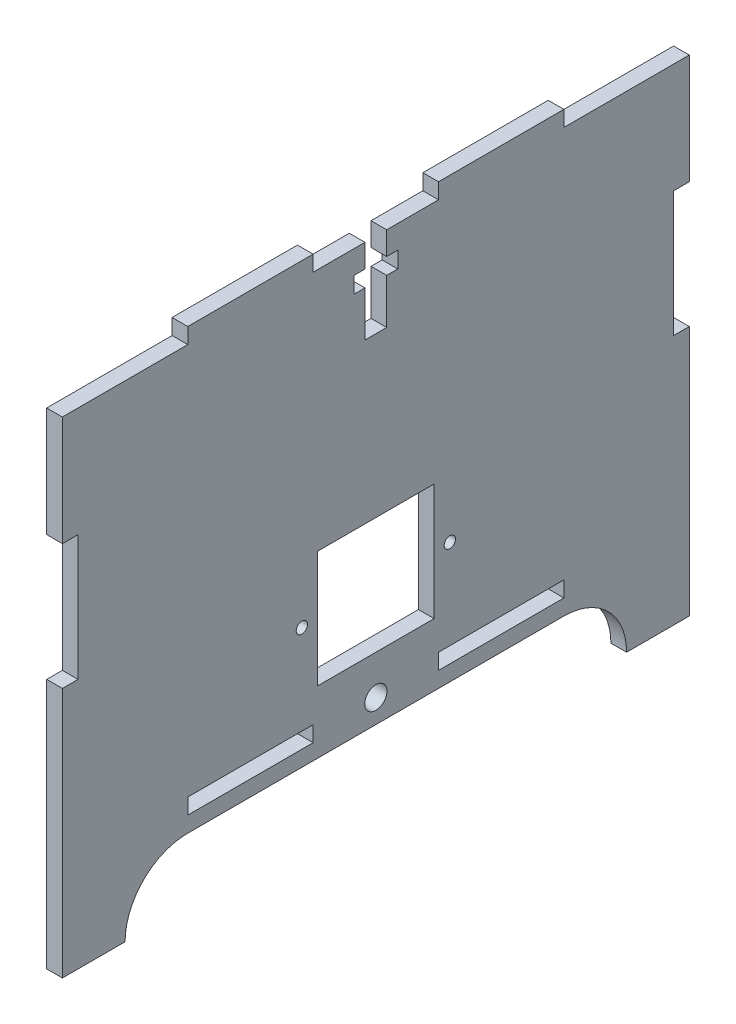
SolidWorks part; units mm, degrees
ref_plane "Front Plane" through (0, 0, 0) normal (0, 0, 1) x (1, 0, 0)
ref_plane "Top Plane" through (0, 0, 0) normal (0, 1, 0) x (1, 0, 0)
ref_plane "Right Plane" through (0, 0, 0) normal (1, 0, 0) x (0, 0, -1)
sketch "Sketch1" plane through (0, 0, 0) normal (1, 0, 0) x (0, 0, -1)
  line L1 (-63.5, 50.8) -> (63.5, 50.8)
  line L2 (-63.5, 50.8) -> (-63.5, -50.8)
  line L3 (-63.5, -50.8) -> (63.5, -50.8)
  line L4 (63.5, 50.8) -> (63.5, -50.8)
  line L5 (-63.5, 50.8) -> (63.5, -50.8) construction
  line L6 (-63.5, -50.8) -> (63.5, 50.8) construction
  point P0 (0, 0)
  dimension "D1" = 127
  dimension "D2" = 101.6
extrude "Boss-Extrude1" add sketch "Sketch1" along normal blind 3.175
sketch "Sketch2" plane through (3.175, 0, 0) normal (1, 0, 0) x (0, 0, -1)
  line L1 (-63.5, 50.8) -> (-38.1, 50.8)
  line L2 (-63.5, 50.8) -> (-63.5, 47.625)
  line L3 (-63.5, 47.625) -> (-38.1, 47.625)
  line L4 (-38.1, 50.8) -> (-38.1, 47.625)
  dimension "D1" = 25.4
  dimension "D2" = 3.175
extrude "Cut-Extrude1" cut sketch "Sketch2" against normal blind 6.35
pattern_linear "LPattern1" count 3 spacing 50.8 along (0, 0, -1) of "Cut-Extrude1"
sketch "Sketch5" plane through (3.175, 0, 0) normal (1, 0, 0) x (0, 0, -1)
  line L0 (-38.1, -50.8) -> (38.1, -50.8) construction
  line L1 (-63.5, -50.8) -> (63.5, -50.8) construction
  line L2 (-38.1, -38.1) -> (38.1, -38.1)
  line L3 (-38.1, -63.5) -> (38.1, -63.5)
  arc A0 (-38.1, -38.1) -> (-38.1, -63.5) centre (-38.1, -50.8) ccw
  arc A1 (38.1, -63.5) -> (38.1, -38.1) centre (38.1, -50.8) ccw
  point P4 (0, -50.8)
  dimension "D2" = 12.7
  dimension "D1" = 76.2
extrude "Cut-Extrude4" cut sketch "Sketch5" against normal blind 6.35
sketch "Sketch8" plane through (3.175, 0, 0) normal (1, 0, 0) x (0, 0, -1)
  line L0 (63.5, -50.8) -> (63.5, 47.625) construction
  line L1 (63.5, 25.4) -> (60.325, 25.4)
  line L2 (63.5, 25.4) -> (63.5, 0)
  line L3 (63.5, 0) -> (60.325, 0)
  line L4 (60.325, 25.4) -> (60.325, 0)
  line L5 (38.1, 50.8) -> (12.7, 50.8) construction
  dimension "D1" = 25.4
  dimension "D2" = 25.4
  dimension "D3" = 3.175
extrude "Cut-Extrude6" cut sketch "Sketch8" against normal blind 6.35
ref_plane "Plane1" through (0, 0, 0) normal (0, 0, 1) x (1, 0, 0)
sketch "Sketch9" plane through (0, 0, 0) normal (-1, 0, 0) x (0, 0, 1)
  line L0 (-63.5, -50.8) -> (-63.5, 0) construction
  line L1 (-38.1, -31.75) -> (-12.7, -31.75)
  line L2 (-38.1, -31.75) -> (-38.1, -34.925)
  line L3 (-38.1, -34.925) -> (-12.7, -34.925)
  line L4 (-12.7, -31.75) -> (-12.7, -34.925)
  line L5 (-38.1, 50.8) -> (-12.7, 50.8) construction
  point P6 (-25.4, 50.8)
  dimension "D1" = 25.4
  dimension "D2" = 3.175
  dimension "D3" = 25.4
  dimension "D4" = 82.55
extrude "Cut-Extrude7" cut sketch "Sketch9" against normal blind 6.35
pattern_linear "LPattern6" count 2 spacing 50.8 along (0, 0, 1) of "Cut-Extrude7"
sketch "Sketch16" plane through (0, 0, 0) normal (-1, 0, 0) x (0, 0, 1)
  line L0 (12.7, 47.625) -> (-12.7, 47.625) construction
  line L1 (-2.1971, 47.625) -> (2.1971, 47.625)
  line L2 (-2.1971, 47.625) -> (-2.1971, 30.48)
  line L3 (-2.1971, 30.48) -> (2.1971, 30.48)
  line L4 (2.1971, 47.625) -> (2.1971, 30.48)
  line L5 (-12.7, 47.625) -> (-12.7, 50.8) construction
  line L7 (-4.445, 42.926) -> (4.445, 42.926)
  line L8 (-4.445, 42.926) -> (-4.445, 39.624)
  line L9 (-4.445, 39.624) -> (4.445, 39.624)
  line L10 (4.445, 42.926) -> (4.445, 39.624)
  point P6 (0, 30.48)
  point P13 (0, 42.926)
  point P14 (4.445, 41.275)
  dimension "D1" = 4.3942
  dimension "D2" = 17.145
  dimension "D3" = 12.7
  dimension "D4" = 3.302
  dimension "D5" = 8.89
  dimension "D6" = 12.7
  dimension "D7" = 6.35
extrude "Cut-Extrude14" cut sketch "Sketch16" against normal blind 6.35 contours L7 L10 L9 L8 | L1 L4 L3 L2
hole_wizard "#8 Clearance Hole1" positions "Sketch18" profile "Sketch17" hole size "#8" standard "ANSI Inch"
sketch "Sketch18" plane through (0, 0, 0) normal (-1, 0, 0) x (0, 0, 1)
  line L3 (-12.7, -34.925) -> (-12.7, -31.75) construction
  line L4 (38.1, -31.75) -> (12.7, -31.75) construction
  point P0 (0, -33.3375)
  point P16 (-12.7, -33.3375)
  dimension "D1" = 12.7
  dimension "D2" = 1.5875
sketch "Sketch17" plane through (0, -33.3375, 0) normal (0, 1, 0) x (0, 0, 1)
  line L0 (0, 0) -> (0, 11.5107)
  line L1 (0, 11.5107) -> (2.2479, 10.16)
  line L2 (2.2479, 10.16) -> (2.2479, 0)
  line L5 (2.2479, 0) -> (0, 0)
  line L10 (0, 11.5107) -> (-2.2479, 10.16) construction
  line L11 (0, -6.35) -> (0, 107.95) construction
  dimension "Hole Dia." = 4.4958
  dimension "Hole Depth" = 10.16
  dimension "Drill Angle" = 118
sketch "Sketch19" plane through (0, 0, 0) normal (-1, 0, 0) x (0, 0, 1)
  line L0 (-49.53, 42.545) -> (-11.43, 42.545) construction
  line L1 (-49.53, 43.815) -> (-11.43, 43.815)
  line L2 (-49.53, 41.275) -> (-11.43, 41.275)
  line L3 (-38.1, 50.8) -> (-38.1, 47.625) construction
  line L4 (-2.1971, 47.625) -> (-12.7, 47.625) construction
  arc A0 (-49.53, 43.815) -> (-49.53, 41.275) centre (-49.53, 42.545) ccw
  arc A1 (-11.43, 41.275) -> (-11.43, 43.815) centre (-11.43, 42.545) ccw
  point P2 (-30.48, 42.545)
  point P7 (-30.48, 43.815)
  dimension "D2" = 1.27
  dimension "D1" = 38.1
  dimension "D3" = 7.62
  dimension "D4" = 3.81
extrude "Cut-Extrude15" [suppressed] cut sketch "Sketch19" against normal blind 6.35
mirror "Mirror2" [suppressed] about plane through (0, 0, 0) normal (0, 0, 1)
pattern_linear "LPattern7" [suppressed] count 5 spacing 5.08
sketch "Sketch20" plane through (0, 0, 0) normal (-1, 0, 0) x (0, 0, 1)
  line L0 (-63.5, -50.8) -> (-63.5, 0) construction
  line L1 (-11.811, -1.778) -> (11.811, -1.778)
  line L2 (-11.811, -1.778) -> (-11.811, -25.4)
  line L3 (-11.811, -25.4) -> (11.811, -25.4)
  line L4 (11.811, -1.778) -> (11.811, -25.4)
  line L5 (38.1, -31.75) -> (12.7, -31.75) construction
  circle A0 centre (-14.986, -13.589) radius 1.143
  circle A1 centre (14.986, -13.589) radius 1.143
  point P4 (0, -25.4)
  point P11 (0, -1.778)
  point P12 (-11.811, -13.589)
  point P15 (11.811, -13.589)
  dimension "D6" = 2.286
  dimension "D7" = 2.286
  dimension "D8" = 14.986
  dimension "D1" = 23.622
  dimension "D2" = 23.622
  dimension "D3" = 63.5
  dimension "D4" = 6.35
  dimension "D5" = 14.986
extrude "Cut-Extrude16" cut sketch "Sketch20" against normal blind 10.16
mirror "Mirror3" about plane through (0, 0, 0) normal (0, 0, 1) of "Cut-Extrude6"
